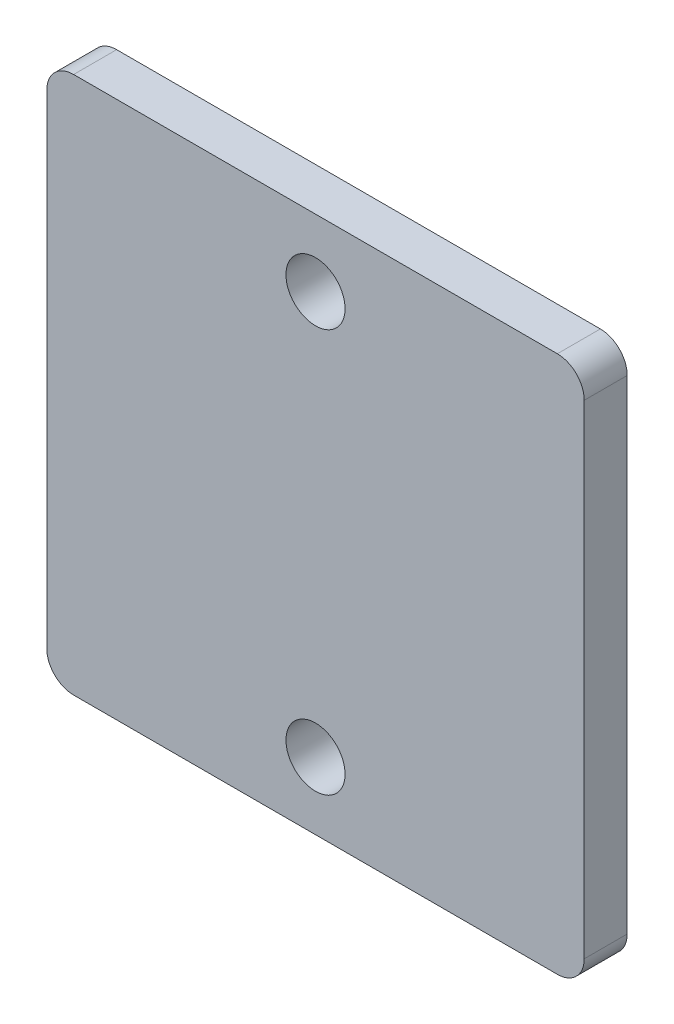
SolidWorks part; units mm, degrees
ref_plane "前视基准面" through (0, 0, 0) normal (0, 0, 1) x (1, 0, 0)
ref_plane "上视基准面" through (0, 0, 0) normal (0, 1, 0) x (1, 0, 0)
ref_plane "右视基准面" through (0, 0, 0) normal (1, 0, 0) x (0, 0, -1)
other "Configuration Table"
sketch "草图1" plane through (0, 0, 0) normal (0, 0, 1) x (1, 0, 0)
  line L0 (-9, -10) -> (9, -10)
  line L1 (10, -9) -> (10, 9)
  line L2 (9, 10) -> (-9, 10)
  line L3 (-10, 9) -> (-10, -9)
  arc A0 (-10, -9) -> (-9, -10) centre (-9, -9) ccw
  arc A1 (9, -10) -> (10, -9) centre (9, -9) ccw
  arc A2 (10, 9) -> (9, 10) centre (9, 9) ccw
  arc A3 (-9, 10) -> (-10, 9) centre (-9, 9) ccw
  circle A4 centre (0, -7.5) radius 1.1
  circle A5 centre (0, 7.5) radius 1.1
extrude "PCB20x20_T1p6_2NPTH_D2p2_pitch15" add sketch "草图1" along normal blind 1.6
